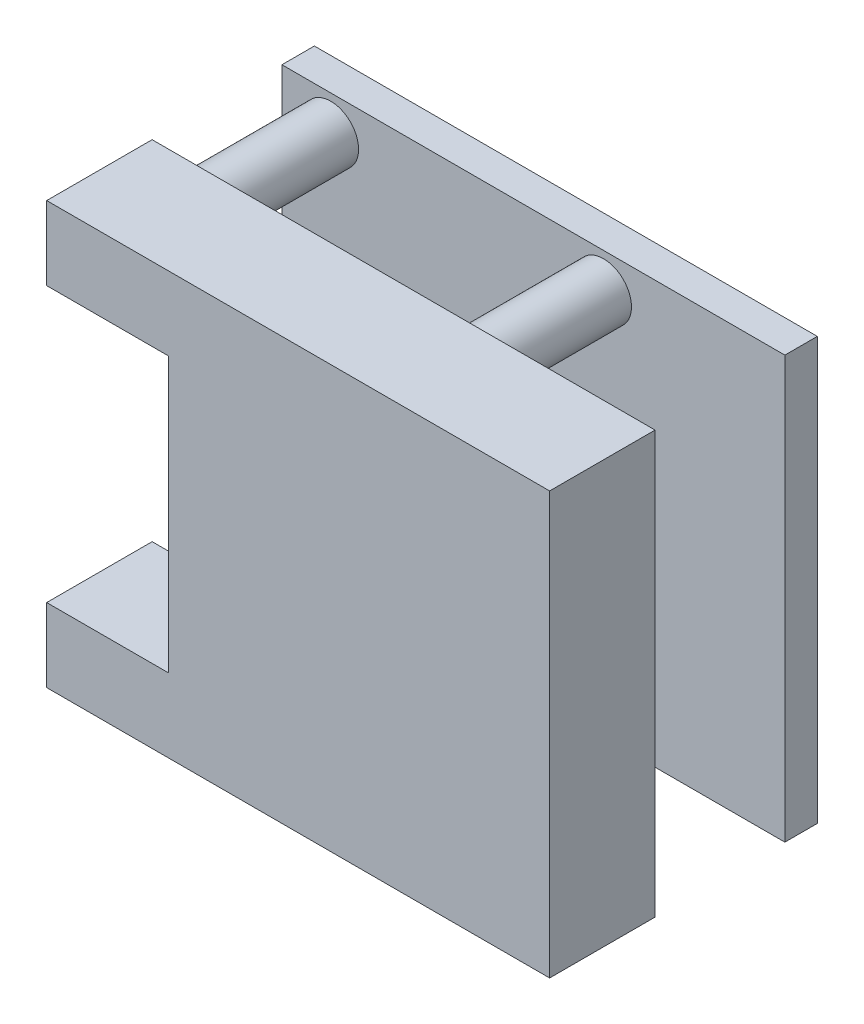
SolidWorks part; units mm, degrees
ref_plane "Front Plane" through (0, 0, 0) normal (0, 0, 1) x (1, 0, 0)
ref_plane "Top Plane" through (0, 0, 0) normal (0, 1, 0) x (1, 0, 0)
ref_plane "Right Plane" through (0, 0, 0) normal (1, 0, 0) x (0, 0, -1)
sketch "Sketch1" plane through (0, 0, 0) normal (0, 0, 1) x (1, 0, 0)
  line L1 (0, 0) -> (31, 0)
  line L2 (0, 0) -> (0, 26)
  line L3 (0, 26) -> (31, 26)
  line L4 (31, 0) -> (31, 26)
  dimension "D1" = 26
  dimension "D2" = 31
extrude "Boss-Extrude1" add sketch "Sketch1" along normal blind 16.5
sketch "Sketch3" plane through (0, 0, 16.5) normal (0, 0, 1) x (1, 0, 0)
  line L0 (0, 0) -> (0, 4.6323)
  line L1 (0, 26) -> (0, 0) construction
  line L2 (0, 4.6323) -> (6.3235, 4.6323)
  line L3 (6.3235, 4.6323) -> (6.3235, 21.3677)
  line L4 (6.3235, 21.3677) -> (0, 21.3677)
  line L5 (0, 21.3677) -> (0, 26)
  line L6 (0, 26) -> (31, 26)
  line L7 (31, 26) -> (31, 0)
  line L8 (31, 0) -> (0, 0)
  line L9 (0, 13) -> (31, 13) construction
  circle A0 centre (3.0103, 2.1581) radius 1.7158
  circle A1 centre (19.8305, 2.1581) radius 1.7158
  circle A2 centre (3.0103, 23.8419) radius 1.7158
  circle A3 centre (19.8305, 23.8419) radius 1.7158
extrude "Cut-Extrude1" cut sketch "Sketch3" against normal blind 8 from offset 6.5 offset against normal yes
sketch "Sketch4" plane through (0, 0, 16.5) normal (0, 0, 1) x (1, 0, 0)
  line L0 (0, 26) -> (0, 0) construction
  line L1 (0, 21.4583) -> (7.5018, 21.4583)
  line L2 (0, 21.4583) -> (0, 4.5417)
  line L3 (0, 4.5417) -> (7.5018, 4.5417)
  line L4 (7.5018, 21.4583) -> (7.5018, 4.5417)
  line L5 (3.7509, 26) -> (3.7509, 21.4583) construction
  line L6 (31, 26) -> (0, 26) construction
  line L7 (3.7509, 21.4583) -> (3.7509, 4.5417) construction
  line L8 (3.7509, 4.5417) -> (3.7509, 0) construction
  line L9 (0, 0) -> (31, 0) construction
extrude "Cut-Extrude2" cut sketch "Sketch4" against normal up to surface (14.5 mm away) up to face at (18.1147, 23.8419, 2)
